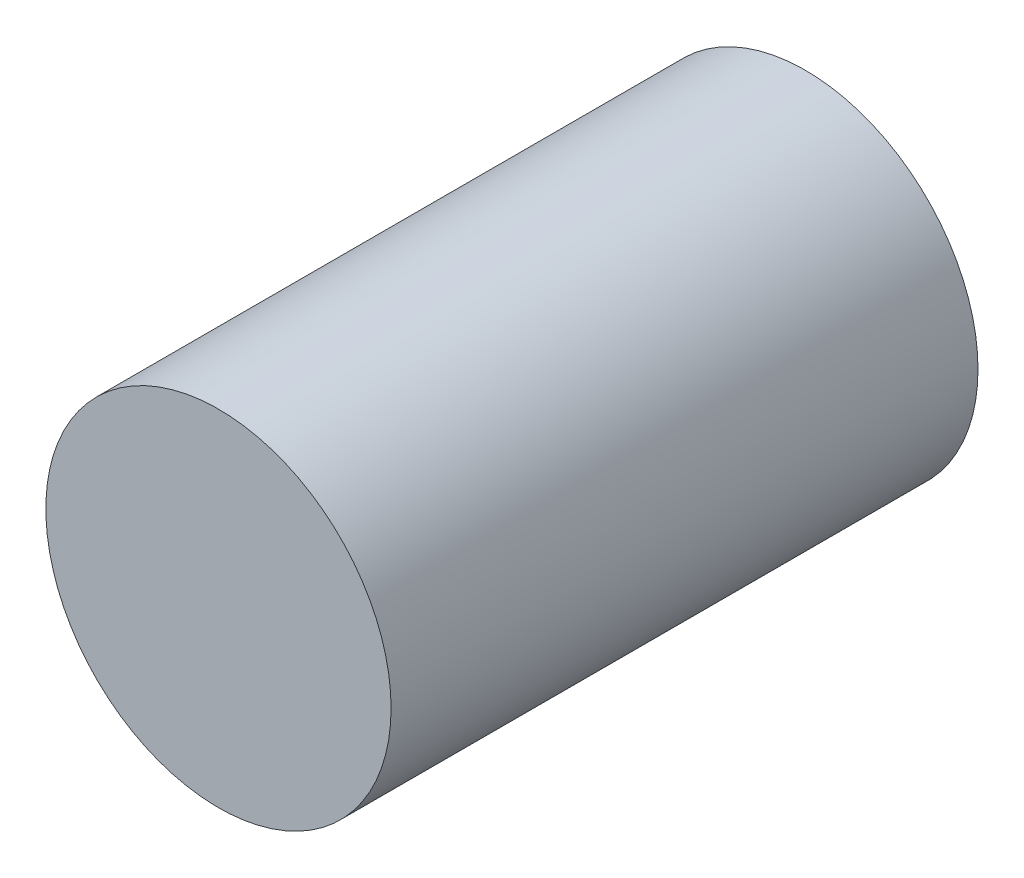
SolidWorks part; units mm, degrees
material "Alloy Steel"
ref_plane "Front Plane" through (0, 0, 0) normal (0, 0, 1) x (1, 0, 0)
ref_plane "Top Plane" through (0, 0, 0) normal (0, 1, 0) x (1, 0, 0)
ref_plane "Right Plane" through (0, 0, 0) normal (1, 0, 0) x (0, 0, -1)
sketch "Sketch1" plane through (0, 0, 0) normal (0, 0, 1) x (1, 0, 0)
  circle A0 centre (0, 0) radius 2.5
  dimension "D1" = 5
extrude "Boss-Extrude1" add sketch "Sketch1" along normal blind 8.5
